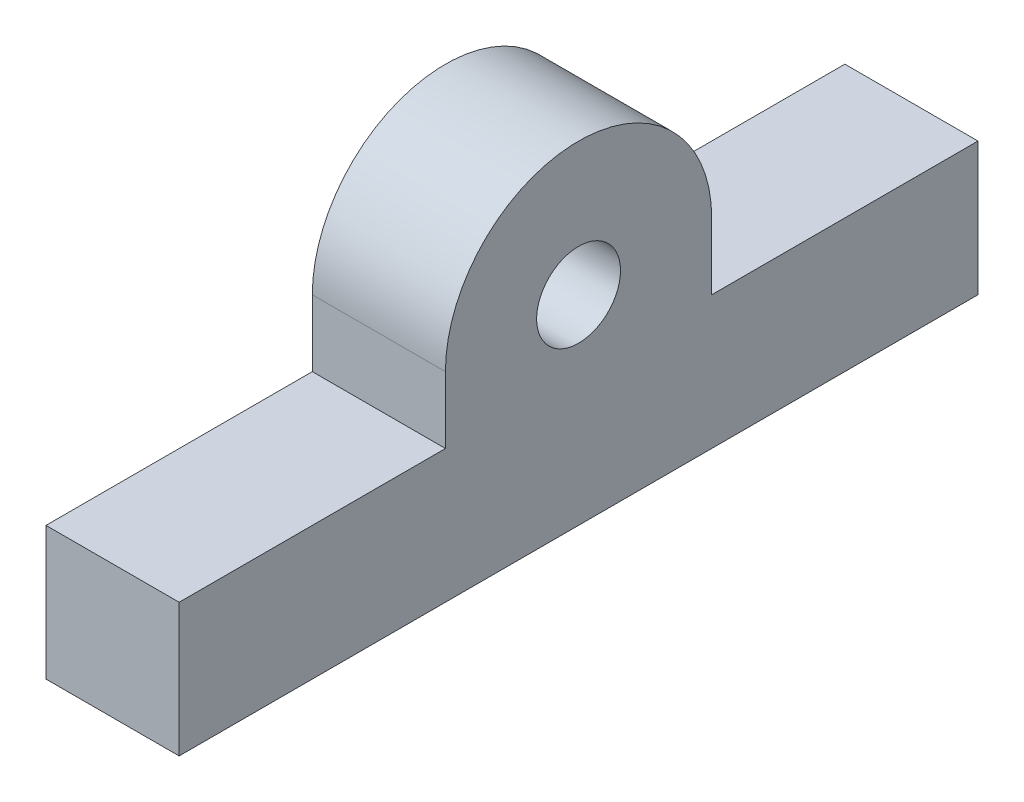
SolidWorks part; units mm, degrees
ref_plane "Front Plane" through (0, 0, 0) normal (0, 0, 1) x (1, 0, 0)
ref_plane "Top Plane" through (0, 0, 0) normal (0, 1, 0) x (1, 0, 0)
ref_plane "Right Plane" through (0, 0, 0) normal (1, 0, 0) x (0, 0, -1)
sketch "Sketch1" plane through (0, 0, 0) normal (1, 0, 0) x (0, 0, -1)
  line L0 (0, 0) -> (76.2, 0)
  line L1 (76.2, 0) -> (76.2, 12.7)
  line L2 (76.2, 12.7) -> (50.8, 12.7)
  line L3 (0, 12.7) -> (0, 0)
  line L5 (50.8, 12.7) -> (50.8, 19.05)
  line L7 (25.4, 19.05) -> (25.4, 12.7)
  line L9 (25.4, 12.7) -> (0, 12.7)
  arc A0 (50.8, 19.05) -> (25.4, 19.05) centre (38.1, 19.05) ccw
  dimension "D1" = 76.2
  dimension "D2" = 12.7
  dimension "D3" = 25.4
  dimension "D4" = 25.4
  dimension "D5" = 6.35
extrude "Boss-Extrude1" add sketch "Sketch1" along normal blind 12.7
sketch "Sketch2" plane through (12.7, 0, 0) normal (1, 0, 0) x (0, 0, -1)
  circle A0 centre (38.1, 19.05) radius 4
  dimension "D1" = 8
extrude "Cut-Extrude1" cut sketch "Sketch2" against normal through all
sketch "Sketch3" plane through (0, 0, 0) normal (0, -1, 0) x (1, 0, 0)
  line L0 (12.7, -76.2) -> (0, -76.2) construction
  line L3 (12.7, 0) -> (0, 0) construction
  circle A0 centre (6.35, -12.7) radius 1.27
  circle A1 centre (6.35, -63.5) radius 1.27
  point P4 (6.35, 0)
  point P10 (6.35, -76.2)
  dimension "D1" = 2.54
  dimension "D4" = 2.54
  dimension "D6" = 12.7
  dimension "D2" = 0
  dimension "D3" = 12.7
  dimension "D5" = 0
  dimension "D7" = 50.8
extrude "Cut-Extrude2" cut sketch "Sketch3" against normal blind 6.35
equation "\"bearing_d\"= 0.5in"
equation "\"heat_set_d\"= 0.1in"
